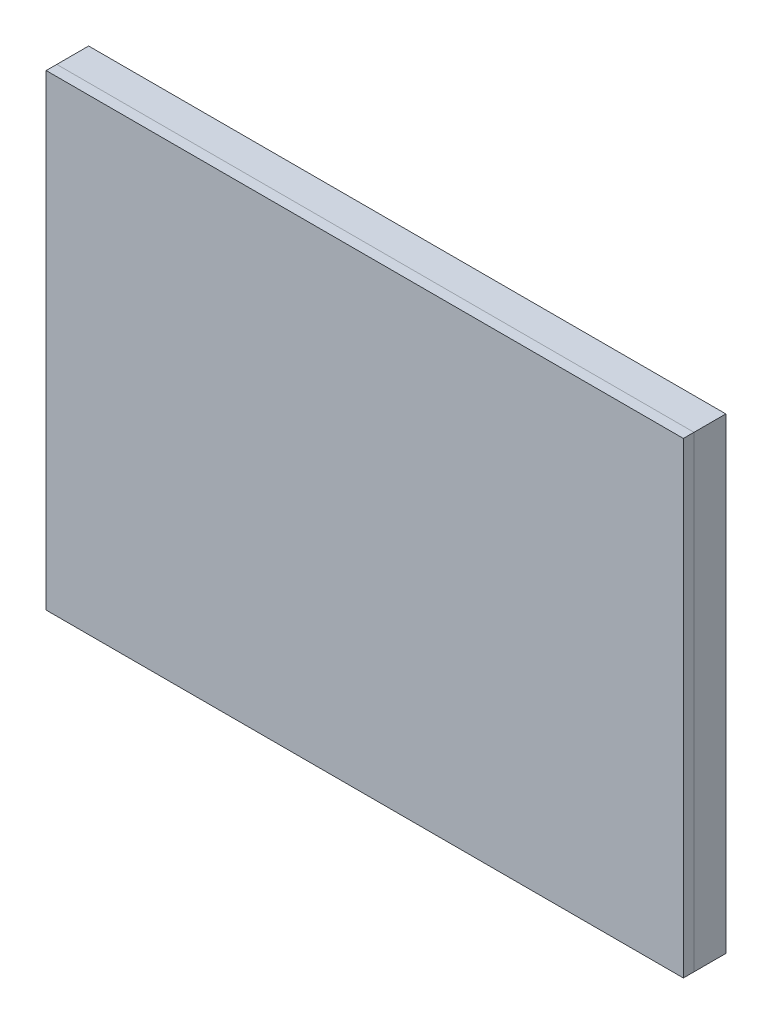
SolidWorks part; units mm, degrees
ref_plane "Front Plane" through (0, 0, 0) normal (0, 0, 1) x (1, 0, 0)
ref_plane "Top Plane" through (0, 0, 0) normal (0, 1, 0) x (1, 0, 0)
ref_plane "Right Plane" through (0, 0, 0) normal (1, 0, 0) x (0, 0, -1)
sketch "Sketch2" plane through (0, 0, 0) normal (0, 0, 1) x (1, 0, 0)
  line L1 (-30, 22) -> (30, 22)
  line L2 (-30, 22) -> (-30, -22)
  line L3 (-30, -22) -> (30, -22)
  line L4 (30, 22) -> (30, -22)
  line L5 (-30, 22) -> (30, -22) construction
  line L6 (-30, -22) -> (30, 22) construction
  point P0 (0, 0)
  dimension "D1" = 60
  dimension "D2" = 44
extrude "Boss-Extrude1" add sketch "Sketch2" along normal blind 3
sketch "Sketch3" plane through (0, 0, 3) normal (0, 0, 1) x (1, 0, 0)
  line L1 (-30, 22) -> (30, 22)
  line L2 (-30, 22) -> (-30, -22)
  line L3 (-30, -22) -> (30, -22)
  line L4 (30, 22) -> (30, -22)
extrude "Boss-Extrude2" add sketch "Sketch3" along normal blind 1 separate body
